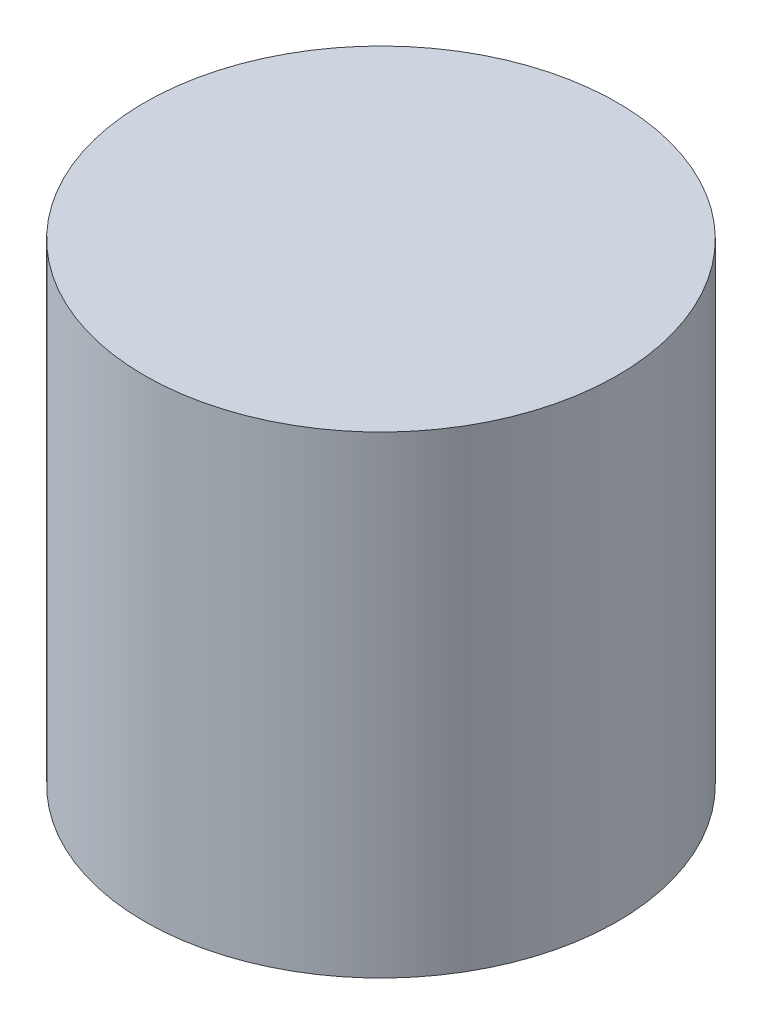
SolidWorks part; units mm, degrees
ref_plane "Front Plane" through (0, 0, 0) normal (0, 0, 1) x (1, 0, 0)
ref_plane "Top Plane" through (0, 0, 0) normal (0, 1, 0) x (1, 0, 0)
ref_plane "Right Plane" through (0, 0, 0) normal (1, 0, 0) x (0, 0, -1)
sketch "Sketch1" plane through (0, 0, 0) normal (0, 1, 0) x (1, 0, 0)
  circle A0 centre (0, 0) radius 31.5
  dimension "D1" = 63
extrude "Boss-Extrude1" add sketch "Sketch1" along normal blind 63
